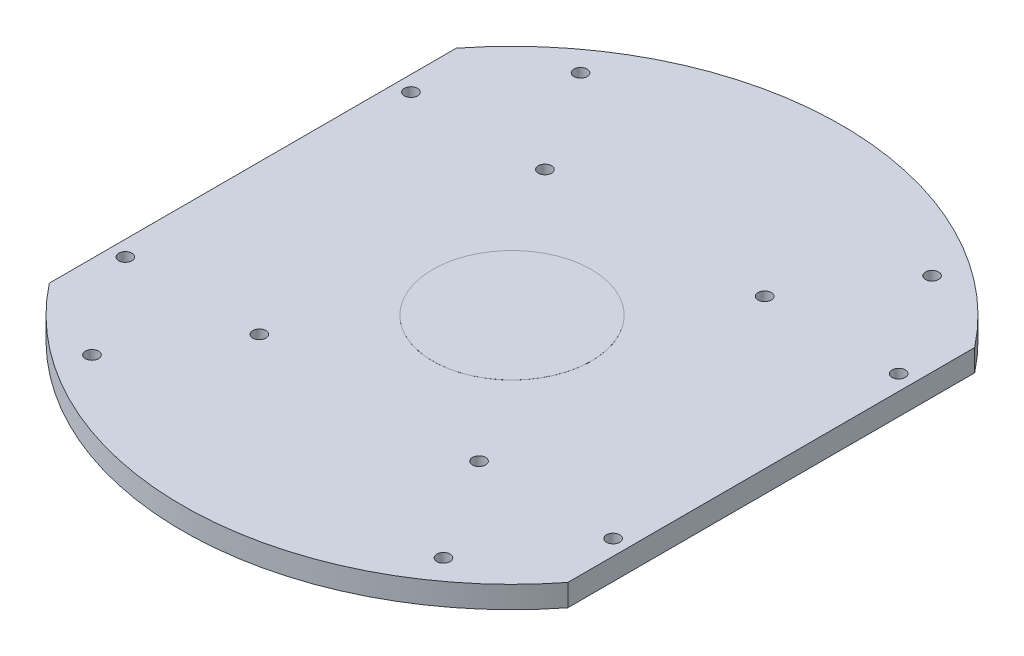
SolidWorks part; units mm, degrees
ref_plane "Front Plane" through (0, 0, 0) normal (0, 0, 1) x (1, 0, 0)
ref_plane "Top Plane" through (0, 0, 0) normal (0, 1, 0) x (1, 0, 0)
ref_plane "Right Plane" through (0, 0, 0) normal (1, 0, 0) x (0, 0, -1)
sketch "Sketch1" plane through (0, 0, 0) normal (0, 1, 0) x (1, 0, 0)
  circle A0 centre (0, 0) radius 75
  dimension "D1" = 150
extrude "Tray" add sketch "Sketch1" along normal blind 5
sketch "Sketch2" plane through (0, 5, 0) normal (0, 1, 0) x (1, 0, 0)
  line L0 (0, 20.7309) -> (0, 0) construction
  line L1 (-40, -55.6) -> (40, -55.6) construction
  line L2 (-40, -55.6) -> (-40, 55.6) construction
  line L3 (-40, 55.6) -> (40, 55.6) construction
  line L4 (40, -55.6) -> (40, 55.6) construction
  line L5 (-40, -55.6) -> (40, 55.6) construction
  line L6 (-40, 55.6) -> (40, -55.6) construction
  line L7 (0, 0) -> (18.5294, 0) construction
  circle A0 centre (-40, 55.6) radius 1.5
  circle A1 centre (40, 55.6) radius 1.5
  circle A2 centre (40, -55.6) radius 1.5
  circle A3 centre (-40, -55.6) radius 1.5
  point P0 (0, 0)
  dimension "D3" = 3
  dimension "D1" = 111.2
  dimension "D2" = 80
extrude "Support Holes" cut sketch "Sketch2" against normal blind 5
sketch "Sketch4" plane through (0, 5, 0) normal (0, 1, 0) x (1, 0, 0)
  line L0 (-55.5, 32.5) -> (-55.5, -32.5) construction
  line L1 (-55.5, -32.5) -> (-25, -32.5) construction
  line L2 (-25, -32.5) -> (-25, 32.5) construction
  line L3 (-25, 32.5) -> (-55.5, 32.5) construction
  line L4 (0, 0) -> (0, 38.5947) construction
  circle A0 centre (-55.5, 32.5) radius 1.5
  circle A1 centre (-25, 32.5) radius 1.5
  circle A2 centre (-55.5, -32.5) radius 1.5
  circle A3 centre (-25, -32.5) radius 1.5
  circle A4 centre (55.5, -32.5) radius 1.5
  circle A5 centre (25, -32.5) radius 1.5
  circle A6 centre (25, 32.5) radius 1.5
  circle A7 centre (55.5, 32.5) radius 1.5
  point P4 (-25, 0)
  dimension "D4" = 3
  dimension "D1" = 30.5
  dimension "D2" = 65
  dimension "D3" = 25
extrude "MotorDriver Holes" cut sketch "Sketch4" against normal blind 5
sketch "Sketch6" plane through (0, 5, 0) normal (0, 1, 0) x (1, 0, 0)
  line L0 (-75, 51.5641) -> (-75, -57.4213) construction
  line L1 (-59, 46.3033) -> (-59, -46.3033)
  line L2 (0, 0) -> (0, 43.9922) construction
  line L3 (59, 46.3033) -> (59, -46.3033)
  line L4 (-59, 51.5641) -> (-59, -57.4213) construction
  circle A0 centre (0, 0) radius 75 construction
  arc A1 (-59, 46.3033) -> (-59, -46.3033) centre (0, 0) ccw
  arc A2 (59, -46.3033) -> (59, 46.3033) centre (0, 0) ccw
  dimension "D1" = 16
extrude "Cut-Extrude1" cut sketch "Sketch6" against normal blind 10
sketch "Sketch7" plane through (0, 5, 0) normal (0, 1, 0) x (1, 0, 0)
  line L0 (-59, 0) -> (59, 0) construction
  line L1 (-59, -46.3033) -> (-59, 46.3033) construction
  line L2 (59, 46.3033) -> (59, -46.3033) construction
  line L3 (0, 75) -> (0, -75) construction
  arc A1 (59, 46.3033) -> (-59, 46.3033) centre (0, 0) ccw construction
  arc A2 (-59, -46.3033) -> (59, -46.3033) centre (0, 0) ccw construction
  circle A3 centre (0, 0) radius 18.0558
extrude "Boss-Extrude1" add sketch "Sketch7" along normal blind 0.01 separate body
